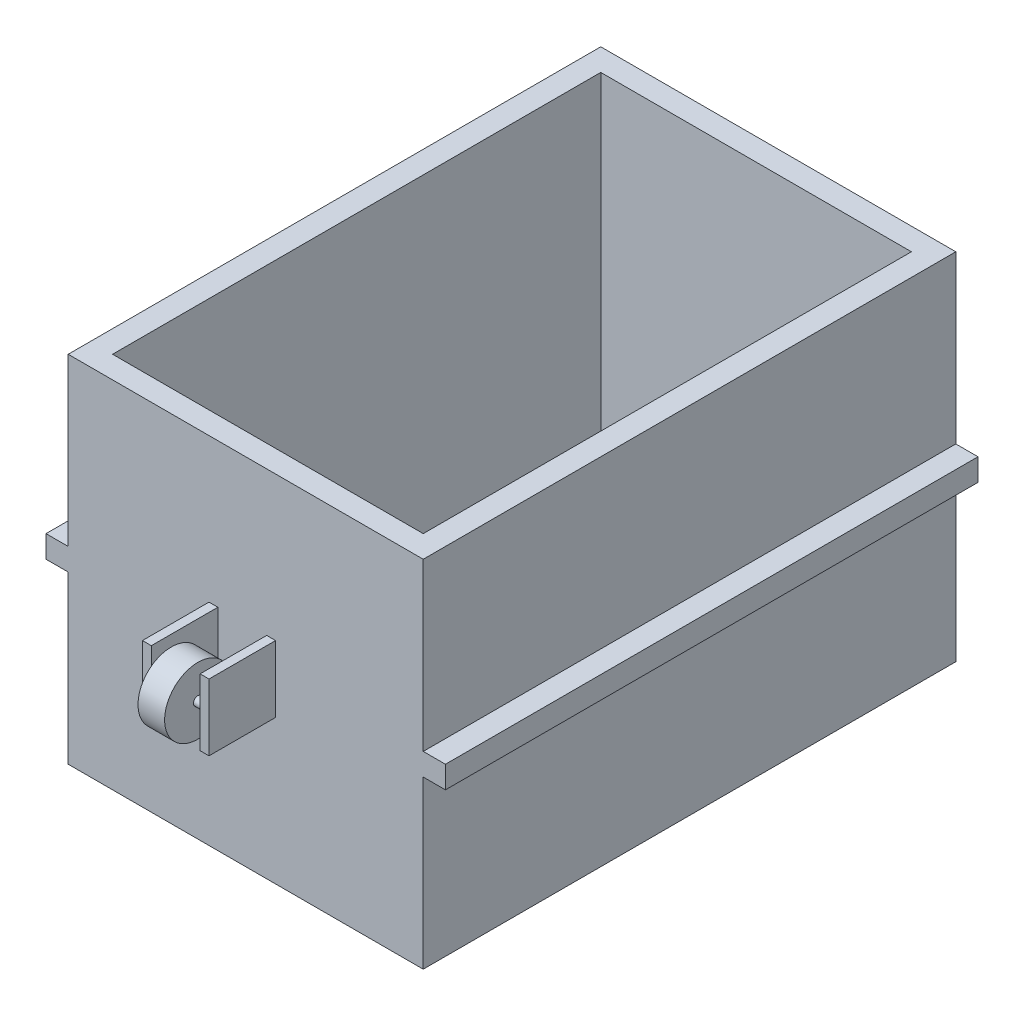
SolidWorks part; units mm, degrees
ref_plane "Front Plane" through (0, 0, 0) normal (0, 0, 1) x (1, 0, 0)
ref_plane "Top Plane" through (0, 0, 0) normal (0, 1, 0) x (1, 0, 0)
ref_plane "Right Plane" through (0, 0, 0) normal (1, 0, 0) x (0, 0, -1)
sketch "Sketch1" plane through (0, 0, 0) normal (0, 0, 1) x (1, 0, 0)
  line L1 (0, 0) -> (400, 0)
  line L2 (0, 0) -> (0, -400)
  line L3 (0, -400) -> (400, -400)
  line L4 (400, 0) -> (400, -400)
  dimension "D1" = 400
  dimension "D2" = 400
extrude "Boss-Extrude1" add sketch "Sketch1" along normal blind 600
sketch "Sketch2" plane through (0, 0, 0) normal (0, 1, 0) x (1, 0, 0)
  line L0 (400, -600) -> (0, -600) construction
  line L1 (375, -575) -> (25, -575)
  line L2 (375, -575) -> (375, -25)
  line L3 (375, -25) -> (25, -25)
  line L4 (25, -575) -> (25, -25)
  line L5 (400, 0) -> (0, 0) construction
  line L6 (0, -600) -> (0, 0) construction
  line L7 (400, -600) -> (400, 0) construction
  dimension "D1" = 25
  dimension "D2" = 25
  dimension "D3" = 25
  dimension "D4" = 25
extrude "Cut-Extrude1" cut sketch "Sketch2" against normal blind 375 contours L2 L1 L4 L3
sketch "Sketch3" plane through (0, 0, 600) normal (0, 0, 1) x (1, 0, 0)
  line L1 (400, -400) -> (400, 0) construction
  line L2 (400, -212.5) -> (425, -212.5)
  line L3 (400, -212.5) -> (400, -187.5)
  line L4 (400, -187.5) -> (425, -187.5)
  line L5 (425, -212.5) -> (425, -187.5)
  line L11 (0, -400) -> (400, -400) construction
  line L13 (200, -400) -> (200, 0) construction
  line L14 (400, 0) -> (0, 0) construction
  line L15 (0, -187.5) -> (-25, -187.5)
  line L16 (-25, -212.5) -> (-25, -187.5)
  line L17 (0, -212.5) -> (-25, -212.5)
  line L18 (0, -212.5) -> (0, -187.5)
  dimension "D1" = 25
  dimension "D2" = 25
  dimension "D3" = 187.5
extrude "Boss-Extrude2" add sketch "Sketch3" against normal blind 600
sketch "Sketch4" plane through (0, 0, 600) normal (0, 0, 1) x (1, 0, 0)
  line L0 (400, 0) -> (0, 0) construction
  line L1 (233.6455, -237.5) -> (158.6455, -237.5)
  line L2 (233.6455, -237.5) -> (233.6455, -162.5)
  line L3 (233.6455, -162.5) -> (158.6455, -162.5)
  line L4 (158.6455, -237.5) -> (158.6455, -162.5)
  dimension "D1" = 75
  dimension "D2" = 75
  dimension "D3" = 162.5
extrude "Boss-Extrude3" add sketch "Sketch4" along normal blind 75
sketch "Sketch5" plane through (0, -162.5, 0) normal (0, 1, 0) x (1, 0, 0)
  line L0 (233.6455, -675) -> (158.6455, -675) construction
  line L1 (223.6455, -675) -> (168.6455, -675)
  line L2 (223.6455, -675) -> (223.6455, -600)
  line L3 (223.6455, -600) -> (168.6455, -600)
  line L4 (168.6455, -675) -> (168.6455, -600)
  line L5 (233.6455, -600) -> (158.6455, -600) construction
  line L6 (158.6455, -675) -> (158.6455, -600) construction
  line L7 (233.6455, -675) -> (233.6455, -600) construction
  dimension "D1" = 10
  dimension "D2" = 10
extrude "Cut-Extrude2" cut sketch "Sketch5" against normal blind 75 contours L2 L1 L4 L3
sketch "Sketch6" plane through (233.6455, 0, 0) normal (1, 0, 0) x (0, 0, -1)
  line L0 (-675, -237.5) -> (-675, -162.5) construction
  line L1 (-675, -237.5) -> (-600, -237.5) construction
  circle A0 centre (-665, -200) radius 37.5
  dimension "D1" = 75
  dimension "D2" = 10
  dimension "D3" = 37.5
extrude "Boss-Extrude4" add sketch "Sketch6" against normal blind 30 from offset 22.5 separate body offset against normal yes
sketch "Sketch7" plane through (211.1455, 0, 0) normal (1, 0, 0) x (0, 0, -1)
  circle A0 centre (-665, -200) radius 5
extrude "Boss-Extrude5" add sketch "Sketch7" along normal blind 22 and the other way blind 44
